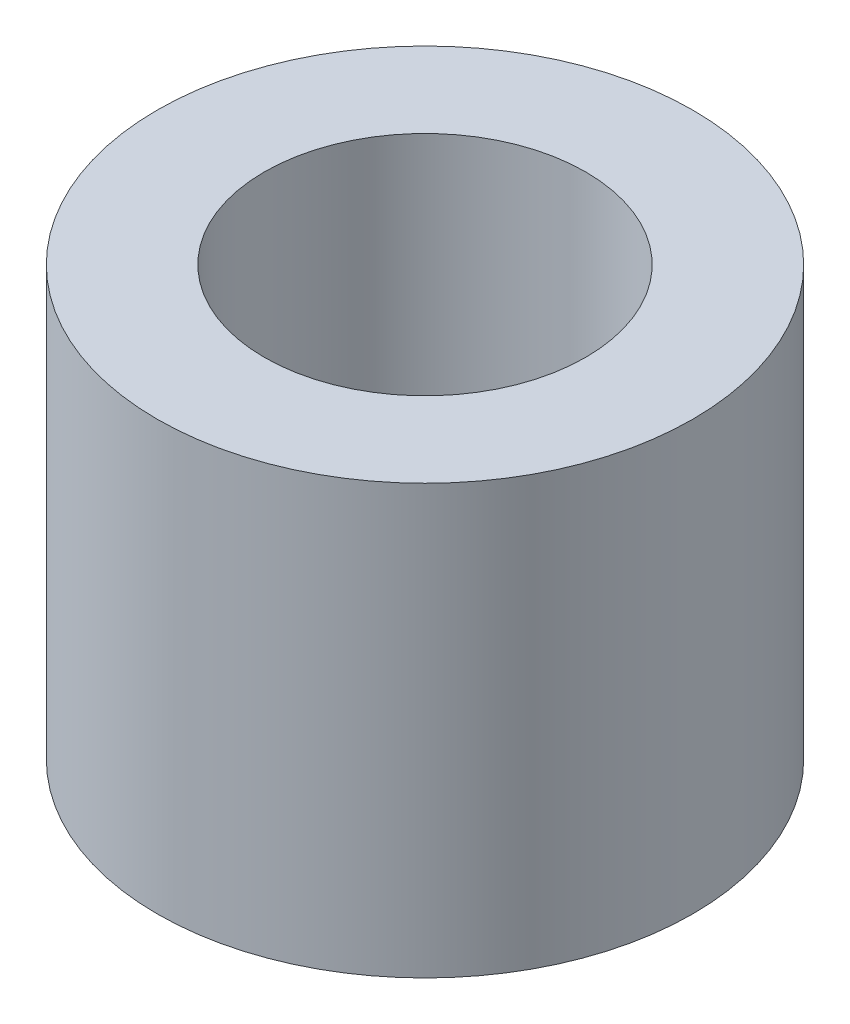
SolidWorks part; units mm, degrees
ref_plane "前视基准面" through (0, 0, 0) normal (0, 0, 1) x (1, 0, 0)
ref_plane "上视基准面" through (0, 0, 0) normal (0, 1, 0) x (1, 0, 0)
ref_plane "右视基准面" through (0, 0, 0) normal (1, 0, 0) x (0, 0, -1)
sketch "草图1" plane through (0, 0, 0) normal (0, 1, 0) x (1, 0, 0)
  circle A0 centre (0, 0) radius 2.5
  circle A1 centre (0, 0) radius 1.5
  dimension "D1" = 5
  dimension "D2" = 3
extrude "凸台-拉伸1" add sketch "草图1" along normal blind 4
